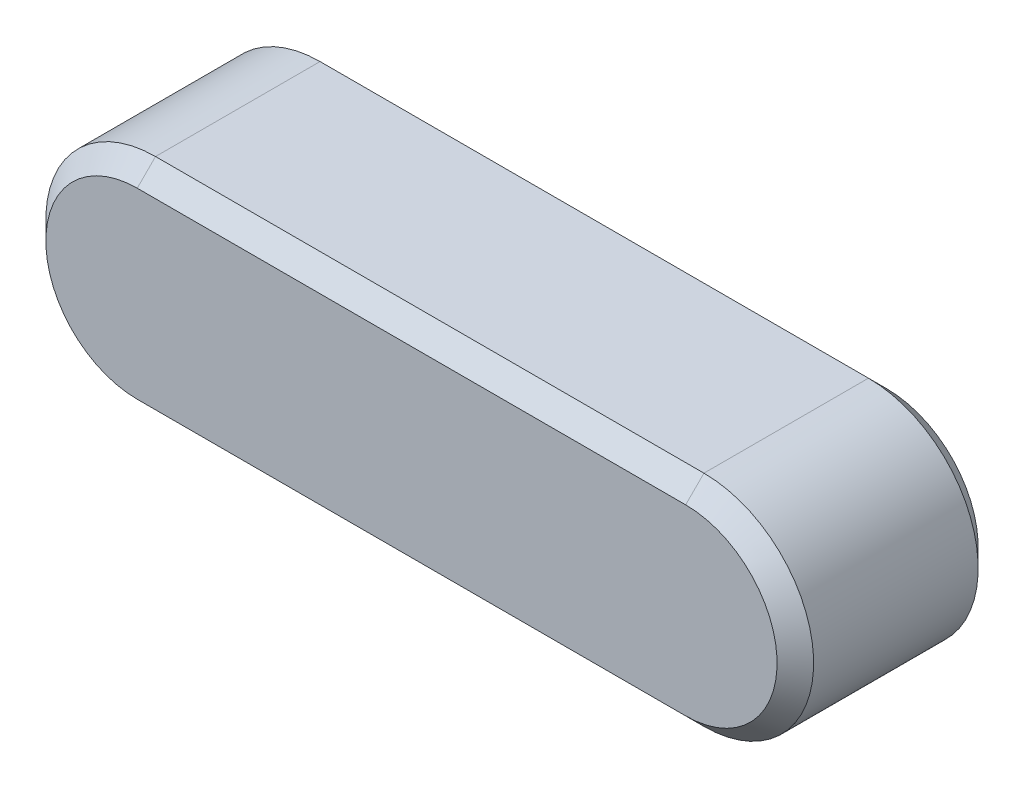
SolidWorks part; units mm, degrees
ref_plane "Front Plane" through (0, 0, 0) normal (0, 0, 1) x (1, 0, 0)
ref_plane "Top Plane" through (0, 0, 0) normal (0, 1, 0) x (1, 0, 0)
ref_plane "Right Plane" through (0, 0, 0) normal (1, 0, 0) x (0, 0, -1)
sketch "Sketch1" plane through (0, 0, 0) normal (0, 0, 1) x (1, 0, 0)
  line L0 (7.5, 0) -> (-7.5, 0) construction
  line L1 (7.5, -3) -> (-7.5, -3)
  line L2 (7.5, 3) -> (-7.5, 3)
  arc A0 (7.5, -3) -> (7.5, 3) centre (7.5, 0) ccw
  arc A1 (-7.5, 3) -> (-7.5, -3) centre (-7.5, 0) ccw
  point P2 (0, 0)
  dimension "D1" = 6
  dimension "D2" = 15
extrude "Boss-Extrude1" add sketch "Sketch1" along normal blind 5.5
chamfer "Chamfer1" distance 0.5 angle 45 8 edges at (0, -3, 0) (10.5, 0, 0) (-10.5, 0, 0) (0, 3, 0) (0, -3, 5.5) (10.5, 0, 5.5) (-10.5, 0, 5.5) (0, 3, 5.5)
